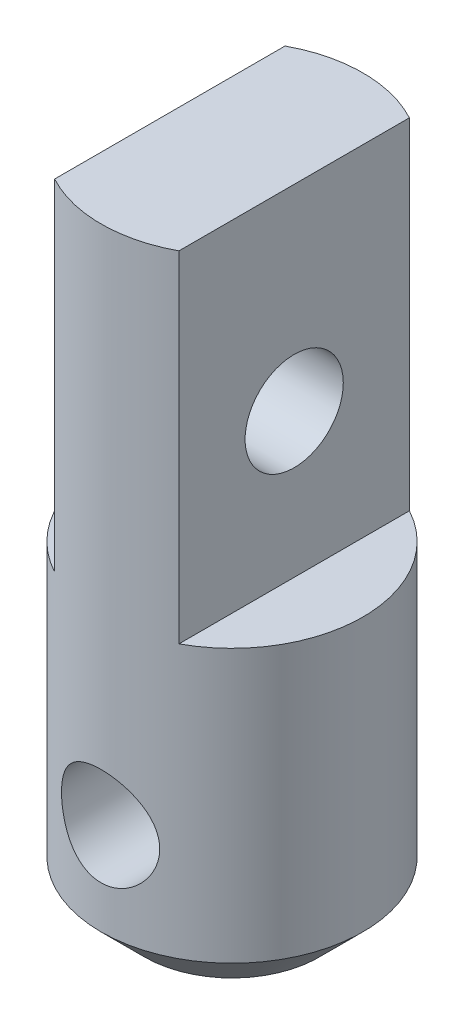
SolidWorks part; units mm, degrees
ref_plane "Front Plane" through (0, 0, 0) normal (0, 0, 1) x (1, 0, 0)
ref_plane "Top Plane" through (0, 0, 0) normal (0, 1, 0) x (1, 0, 0)
ref_plane "Right Plane" through (0, 0, 0) normal (1, 0, 0) x (0, 0, -1)
sketch "Sketch2" plane through (0, 0, 0) normal (0, 1, 0) x (1, 0, 0)
  circle A0 centre (0, 0) radius 6
  dimension "D1" = 12
extrude "Boss-Extrude1" add sketch "Sketch2" along normal blind 14.5 contours A0
chamfer "Chamfer1" distance 2 angle 45 1 edges at (0, 0, 6)
sketch "Sketch3" plane through (0, 14.5, 0) normal (0, 1, 0) x (1, 0, 0)
  line L0 (-2.85, 0) -> (-2.85, 5.2799)
  line L1 (-2.85, 0) -> (2.85, 0) construction
  line L2 (-2.85, 0) -> (-2.85, -5.2799)
  line L4 (2.85, 5.2799) -> (2.85, -5.2799)
  arc A1 (-2.85, -5.2799) -> (2.85, -5.2799) centre (0, 0) ccw
  arc A2 (2.85, 5.2799) -> (-2.85, 5.2799) centre (0, 0) ccw
  dimension "D1" = 12
  dimension "D2" = 5.7
  dimension "D3" = 5.7
extrude "Boss-Extrude3" add sketch "Sketch3" along normal blind 15.6 contours L2 A1 L4 A2 L0
sketch "Sketch4" plane through (2.85, 0, 0) normal (1, 0, 0) x (0, 0, -1)
  line L0 (0, 14.5) -> (0, 21.1) construction
  line L1 (5.2799, 14.5) -> (-5.2799, 14.5) construction
  circle A0 centre (0, 21.1) radius 2.1
  point P1 (0, 21.1)
  point P8 (0, 21.1)
  dimension "D2" = 4.2
  dimension "D1" = 6.6
ref_plane "Plane1" through (0, 0, 6) normal (0, 0, 1) x (1, 0, 0)
sketch "Sketch6" plane through (0, 0, 6) normal (0, 0, 1) x (1, 0, 0)
  line L0 (0, 0) -> (0, 6.2) construction
  line L1 (-4, 0) -> (4, 0) construction
  circle A0 centre (0, 6.2) radius 2.1
  point P1 (0, 6.2)
  point P7 (0, 6.2)
  dimension "D2" = 4.2
  dimension "D1" = 6.2
hole_wizard "M4 Clearance Hole1" positions "Sketch6" profile "Sketch7" hole size "M4" standard "ANSI Metric" end condition through all
sketch "Sketch7" plane through (0, 6.2, 6) normal (1, 0, 0) x (0, -1, 0)
  line L0 (0, 0) -> (0, 12)
  line L1 (0, 12) -> (2.25, 12)
  line L2 (2.25, 12) -> (2.25, 0)
  line L5 (2.25, 0) -> (0, 0)
  line L11 (0, -6.35) -> (0, 107.95) construction
  dimension "Thru Hole Dia." = 4.5
  dimension "Thru Hole Depth" = 12
hole_wizard "M4 Clearance Hole2" positions "Sketch4" profile "Sketch8" hole size "M4" standard "ANSI Metric" end condition through all
sketch "Sketch8" plane through (2.85, 21.1, 0) normal (0, 1, 0) x (0, 0, -1)
  line L0 (0, 0) -> (0, 8.85)
  line L1 (0, 8.85) -> (2.25, 8.85)
  line L2 (2.25, 8.85) -> (2.25, 0)
  line L5 (2.25, 0) -> (0, 0)
  line L11 (0, -6.35) -> (0, 107.95) construction
  dimension "Thru Hole Dia." = 4.5
  dimension "Thru Hole Depth" = 8.85
